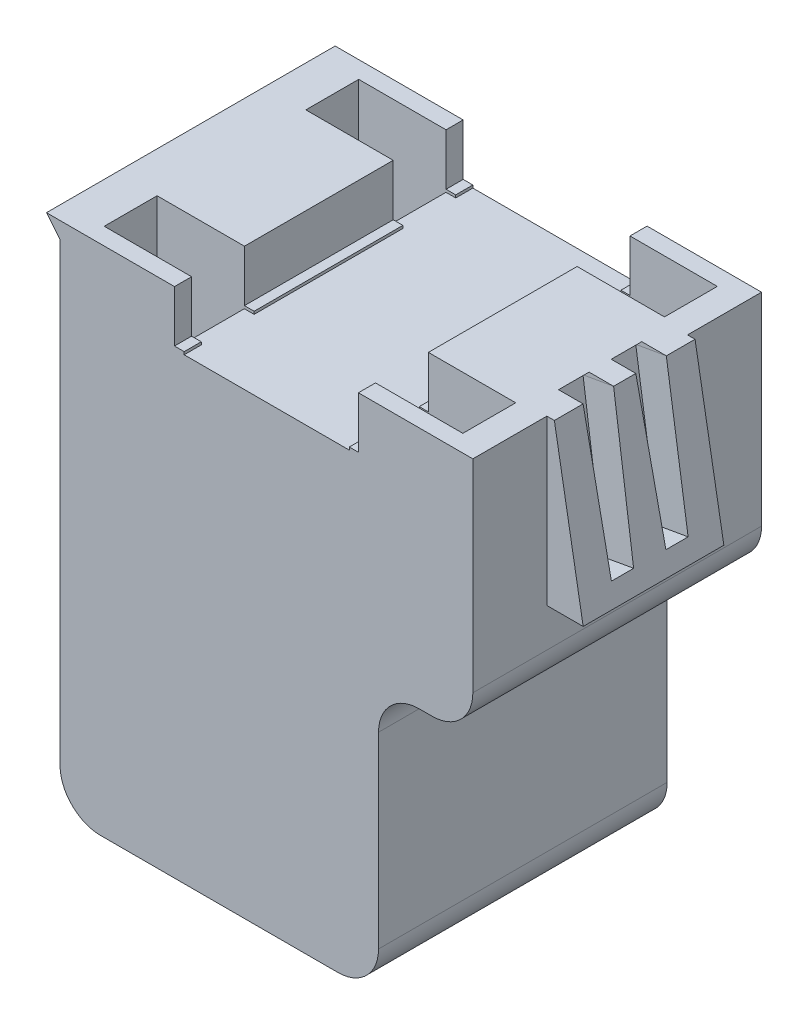
SolidWorks part; units mm, degrees
ref_plane "Alzado" through (0, 0, 0) normal (0, 0, 1) x (1, 0, 0)
ref_plane "Planta" through (0, 0, 0) normal (0, 1, 0) x (1, 0, 0)
ref_plane "Vista lateral" through (0, 0, 0) normal (1, 0, 0) x (0, 0, -1)
sketch "Croquis1" plane through (0, 0, 0) normal (0, 0, 1) x (1, 0, 0)
  line L1 (-15.23, 18.9) -> (-6.785, 18.9)
  line L2 (-15.23, 18.9) -> (-15.23, -15.9)
  line L3 (-12.23, -18.9) -> (5.27, -18.9)
  line L4 (15.23, 18.9) -> (15.23, 3.95)
  line L5 (-15.23, 18.9) -> (8.27, -10.2628) construction
  line L6 (-15.23, -18.9) -> (15.23, 18.9) construction
  line L7 (-6.785, 15.1) -> (6.785, 15.1)
  line L8 (-6.785, 15.1) -> (-6.785, 18.9)
  line L9 (6.785, 15.1) -> (6.785, 18.9)
  line L10 (6.785, 18.9) -> (15.23, 18.9)
  line L11 (8.27, -15.9) -> (8.27, -2.05)
  line L12 (11.27, 0.95) -> (12.23, 0.95)
  arc A0 (15.23, 3.95) -> (12.23, 0.95) centre (12.23, 3.95) cw
  arc A1 (11.27, 0.95) -> (8.27, -2.05) centre (11.27, -2.05) ccw
  arc A2 (5.27, -18.9) -> (8.27, -15.9) centre (5.27, -15.9) ccw
  arc A3 (-12.23, -18.9) -> (-15.23, -15.9) centre (-12.23, -15.9) cw
  point P0 (0, 0)
  point P17 (8.27, 0.95)
  point P20 (8.27, -18.9)
  dimension "D1" = 3
  dimension "D2" = 30.46
  dimension "D4" = 19.85
extrude "Saliente-Extruir1" add sketch "Croquis1" along normal blind 21.3
sketch "Croquis2" plane through (0, 0, 0) normal (0, 0, -1) x (-1, 0, 0)
  line L0 (-15.23, 18.9) -> (-15.7844, 18.9)
  line L1 (-15.7844, 18.9) -> (-17.91, 6.8)
  line L2 (-15.23, 6.8) -> (-17.91, 6.8)
  line L3 (-15.23, 3.95) -> (-15.23, 18.9) construction
  line L4 (-15.23, 18.9) -> (-15.23, 6.8)
extrude "Saliente-Extruir2" add sketch "Croquis2" against normal through all
sketch "Croquis3" plane through (0, 0, 0) normal (0, 0, -1) x (-1, 0, 0)
  line L0 (-15.23, 6.8) -> (-15.23, 18.9)
  line L1 (-15.7844, 18.9) -> (-6.785, 18.9) construction
  line L2 (-15.23, 18.9) -> (-15.7844, 18.9)
  line L3 (-15.7844, 18.9) -> (-17.91, 6.8)
  line L4 (-17.91, 6.8) -> (-15.23, 6.8)
extrude "Cortar-Extruir1" cut sketch "Croquis3" against normal blind 5.46
sketch "Croquis4" plane through (0, 0, 21.3) normal (0, 0, 1) x (1, 0, 0)
  line L0 (17.91, 6.8) -> (15.23, 6.8)
  line L1 (17.91, 6.8) -> (15.7844, 18.9)
  line L2 (15.23, 6.8) -> (15.23, 18.9)
  line L3 (15.23, 18.9) -> (15.7844, 18.9)
extrude "Cortar-Extruir3" cut sketch "Croquis4" against normal blind 5.46
sketch "Croquis5" plane through (18.5326, 3.2556, 0) normal (0.9849, 0.173, 0) x (0, 0, -1)
  line L0 (-13.72, 15.8839) -> (-13.72, 16.1973)
  line L3 (-15.84, 15.8839) -> (-5.46, 15.8839) construction
  line L4 (-13.72, 16.1973) -> (-11.47, 16.1973)
  line L6 (-11.47, 16.1973) -> (-11.47, 15.8839)
  line L7 (-9.83, 15.8839) -> (-9.83, 16.1973)
  line L8 (-13.72, 15.8839) -> (-13.48, 5.1987)
  line L9 (-13.48, 5.1987) -> (-11.84, 5.1987)
  line L10 (-7.58, 15.8839) -> (-7.82, 5.1987)
  line L11 (-7.82, 5.1987) -> (-9.46, 5.1987)
  line L12 (-9.83, 16.1973) -> (-7.58, 16.1973)
  line L13 (-11.47, 15.8839) -> (-11.84, 5.1987)
  line L14 (-9.83, 15.8839) -> (-9.46, 5.1987)
  line L15 (-7.58, 16.1973) -> (-7.58, 15.8839)
  dimension "D4" = 1.64
extrude "Cortar-Extruir4" cut sketch "Croquis5" against normal blind 2.29
sketch "Croquis6" plane through (0, 18.9, 0) normal (0, 1, 0) x (1, 0, 0)
  line L2 (13.23, -20.0378) -> (13.23, -16.1378)
  line L3 (-13.23, -1.2622) -> (-6.0702, -1.2622)
  line L4 (-13.23, -1.2622) -> (-13.23, -5.1622)
  line L5 (-13.23, -5.1622) -> (-6.0702, -5.1622)
  line L6 (13.23, -1.2622) -> (13.23, -5.1622)
  line L8 (-13.23, -16.1378) -> (-6.0702, -16.1378)
  line L9 (-13.23, -20.0378) -> (-13.23, -16.1378)
  line L10 (-13.23, -20.0378) -> (-6.0702, -20.0378)
  line L11 (6.785, 0) -> (-6.785, 0) construction
  line L12 (-6.0702, 0) -> (6.1154, 0)
  line L13 (-6.0702, 0) -> (-6.0702, -1.2622)
  line L14 (-6.0702, -21.7081) -> (6.1154, -21.7081)
  line L15 (6.1154, 0) -> (6.1154, -1.2622)
  line L16 (-6.0702, -5.1622) -> (-6.0702, -16.1378)
  line L17 (6.1154, -1.2622) -> (13.23, -1.2622)
  line L18 (6.1154, -5.1622) -> (13.23, -5.1622)
  line L19 (6.1154, -16.1378) -> (13.23, -16.1378)
  line L20 (-6.0702, -20.0378) -> (-6.0702, -21.7081)
  line L21 (6.1154, -20.0378) -> (13.23, -20.0378)
  line L22 (6.1154, -20.0378) -> (6.1154, -21.7081)
  line L23 (6.1154, -5.1622) -> (6.1154, -16.1378)
  dimension "D1" = 3.9
extrude "Cortar-Extruir5" cut sketch "Croquis6" against normal blind 4
sketch "Croquis7" plane through (0, 14.9, 0) normal (0, 1, 0) x (1, 0, 0)
  line L1 (-13.23, -5.1622) -> (-6.0702, -5.1622) construction
  line L2 (-13.23, -1.2622) -> (-6.7921, -1.2622)
  line L3 (-13.23, -1.2622) -> (-13.23, -5.1622)
  line L4 (-13.23, -5.1622) -> (-6.7921, -5.1622)
  line L5 (-6.7921, -1.2622) -> (-6.7921, -5.1622)
  line L6 (13.23, -1.2622) -> (6.1154, -1.2622) construction
  line L7 (6.785, -1.2622) -> (13.23, -1.2622)
  line L8 (6.785, -1.2622) -> (6.785, -5.1622)
  line L9 (6.785, -5.1622) -> (13.23, -5.1622)
  line L10 (13.23, -1.2622) -> (13.23, -5.1622)
  line L11 (6.1154, -1.2622) -> (6.785, -1.2622) construction
  line L13 (13.23, -20.0378) -> (13.23, -16.1378)
  line L14 (6.785, -16.1378) -> (13.23, -16.1378)
  line L15 (6.785, -20.0378) -> (6.785, -16.1378)
  line L16 (6.785, -20.0378) -> (13.23, -20.0378)
  line L17 (-6.7921, -20.0378) -> (-6.7921, -16.1378)
  line L18 (-13.23, -16.1378) -> (-6.7921, -16.1378)
  line L19 (-13.23, -20.0378) -> (-13.23, -16.1378)
  line L20 (-13.23, -20.0378) -> (-6.7921, -20.0378)
extrude "Cortar-Extruir6" cut sketch "Croquis7" against normal blind 12
sketch "Croquis10" plane through (0, 0, 21.3) normal (0, 0, 1) x (1, 0, 0)
  line L0 (-15.23, 18.9) -> (-16.23, 18.9)
  line L1 (-16.23, 18.9) -> (-15.23, 17.6719)
  line L2 (-15.23, 18.9) -> (-15.23, -15.9) construction
  line L17 (6.785, 15.1) -> (6.1154, 15.1)
  line L18 (6.1154, 15.1) -> (6.1154, 14.9)
  line L19 (6.1154, 14.9) -> (-6.0702, 14.9)
  line L20 (-6.0702, 14.9) -> (-6.0702, 15.1)
  line L21 (-6.0702, 15.1) -> (-6.785, 15.1)
  line L22 (-6.785, 15.1) -> (-6.785, 18.9)
  line L23 (-6.785, 18.9) -> (-15.23, 18.9)
  line L24 (-15.23, 18.9) -> (-15.23, -15.9)
  line L25 (-12.23, -18.9) -> (5.27, -18.9)
  line L26 (8.27, -15.9) -> (8.27, -2.05)
  line L27 (11.27, 0.95) -> (12.23, 0.95)
  line L28 (15.23, 3.95) -> (15.23, 18.9)
  line L29 (15.23, 18.9) -> (6.785, 18.9)
  line L30 (6.785, 18.9) -> (6.785, 15.1)
  line L38 (-15.23, 18.9) -> (-15.23, 17.6719)
  arc A4 (-15.23, -15.9) -> (-12.23, -18.9) centre (-12.23, -15.9) ccw
  arc A5 (5.27, -18.9) -> (8.27, -15.9) centre (5.27, -15.9) ccw
  arc A6 (11.27, 0.95) -> (8.27, -2.05) centre (11.27, -2.05) ccw
  arc A7 (12.23, 0.95) -> (15.23, 3.95) centre (12.23, 3.95) ccw
  dimension "D1" = 1
  dimension "D2" = 0
extrude "Saliente-Extruir3" add sketch "Croquis10" against normal through all
sketch "Croquis11" plane through (0, 0, 0) normal (0, 0, -1) x (-1, 0, 0)
  line L0 (0, -3.8906) -> (10.1881, -3.8906) construction
  text T0 "SCT013" font "Century Gothic" height in points 7
extrude "Cortar-Extruir8" cut sketch "Croquis11" against normal blind 0.01
sketch "Croquis13" plane through (0, 0, 0) normal (0, 0, -1) x (-1, 0, 0)
  line L0 (-5.0354, -7.5851) -> (11.1754, -7.5851) construction
  text T0 "   100A : 50 mA" font "Century Gothic" height in points 6
extrude "Cortar-Extruir10" cut sketch "Croquis13" against normal blind 0.01
ref_point "Punto1"
ref_plane "Plano6" through (0, 0, 10.65) normal (0, 0, -1) x (-1, 0, 0)
sketch "Croquis24" plane through (0, 0, 10.65) normal (0, 0, -1) x (-1, 0, 0)
  spline S0 degree 3 poles (9.6199, -18.9) (6.344, -37.1232) (25.9288, -34.7825) (74.1833, -24.0324) (77.5295, -44.1652) knots 0 0 0 0 0.529362 1 1 1 1
sketch "Croquis25" plane through (0, -18.9, 0) normal (0, -1, 0) x (1, 0, 0)
  circle A0 centre (-9.6199, 10.65) radius 1
  dimension "D1" = 2
sketch "Sketch1" plane through (0, -18.9, 0) normal (0, -1, 0) x (1, 0, 0)
  circle A0 centre (-2.3947, 10.9079) radius 3
  dimension "D1" = 6
extrude "Cut-Extrude1" cut sketch "Sketch1" against normal blind 10
